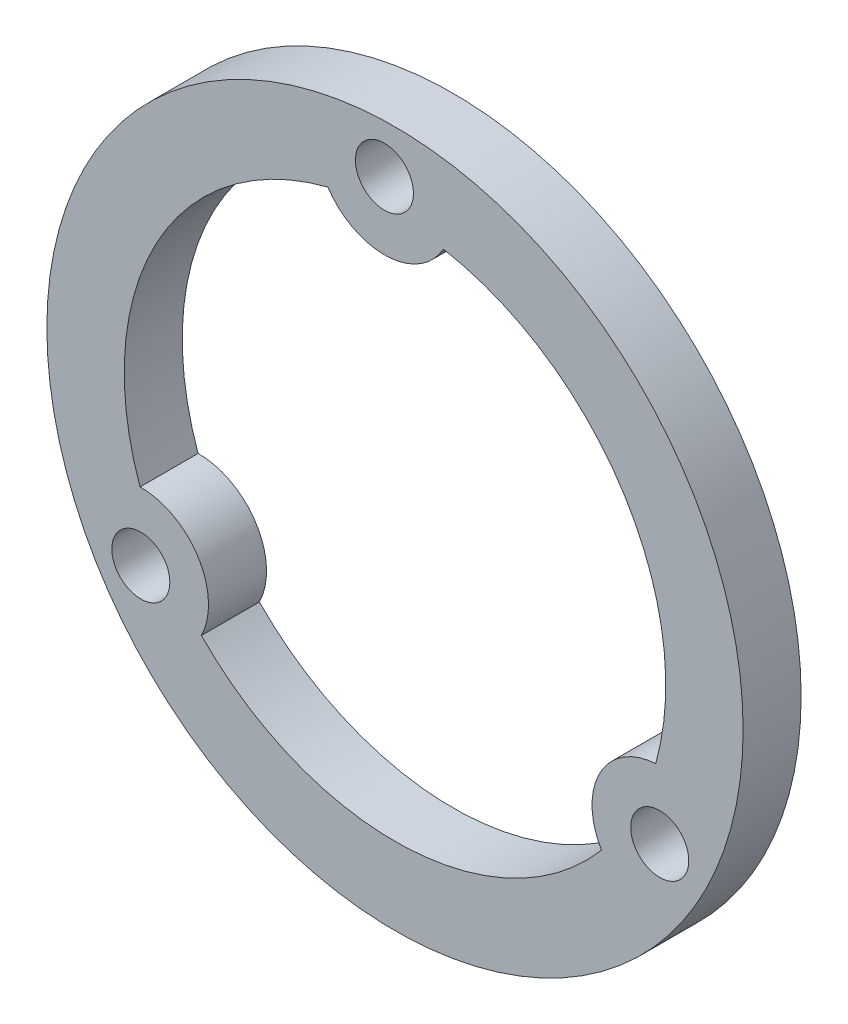
SolidWorks part; units mm, degrees
ref_plane "Plan de face" through (0, 0, 0) normal (0, 0, 1) x (1, 0, 0)
ref_plane "Plan de dessus" through (0, 0, 0) normal (0, 1, 0) x (1, 0, 0)
ref_plane "Plan de droite" through (0, 0, 0) normal (1, 0, 0) x (0, 0, -1)
sketch "Esquisse1" plane through (0, 0, 0) normal (0, 0, 1) x (1, 0, 0)
  line L0 (-0.5467, 15.4904) -> (-13.1417, -8.2186) construction
  line L1 (-13.1417, -8.2186) -> (13.6884, -7.2717) construction
  line L2 (13.6884, -7.2717) -> (-0.5467, 15.4904) construction
  circle A0 centre (0, 0) radius 18
  circle A2 centre (-0.5467, 15.4904) radius 1.5
  circle A3 centre (-13.1417, -8.2186) radius 1.5
  circle A4 centre (13.6884, -7.2717) radius 1.5
  arc A5 (-3.4686, 13.5635) -> (2.5037, 13.7743) centre (-0.5467, 15.4904) ccw
  arc A6 (-10.0121, -9.7856) -> (-13.1808, -4.7189) centre (-13.1417, -8.2186) ccw
  arc A7 (13.4806, -3.7779) -> (10.677, -9.0554) centre (13.6884, -7.2717) ccw
  arc A8 (-10.0121, -9.7856) -> (10.677, -9.0554) centre (0, 0) ccw
  arc A9 (-3.4686, 13.5635) -> (-13.1808, -4.7189) centre (0, 0) ccw
  arc A10 (13.4806, -3.7779) -> (2.5037, 13.7743) centre (0, 0) ccw
  circle A11 centre (0, 0) radius 14 construction
  dimension "D1" = 36
  dimension "D3" = 3
  dimension "D4" = 3
  dimension "D5" = 3
  dimension "D8" = 15.5
  dimension "D9" = 15.5
  dimension "D10" = 15.5
  dimension "D11" = 7
  dimension "D12" = 7
  dimension "D13" = 7
  dimension "D6" = 60
  dimension "D7" = 60
extrude "Boss.-Extru.2" add sketch "Esquisse1" along normal blind 3
